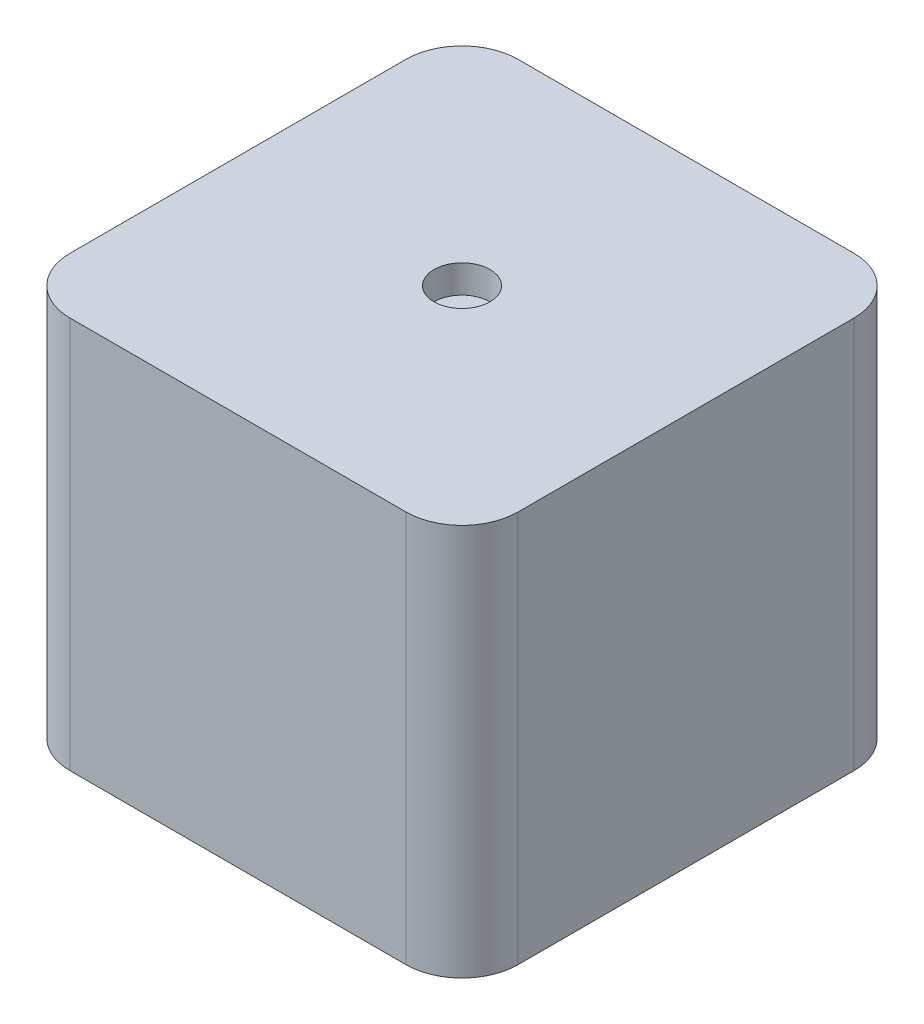
SolidWorks part; units mm, degrees
ref_plane "Front Plane" through (0, 0, 0) normal (0, 0, 1) x (1, 0, 0)
ref_plane "Top Plane" through (0, 0, 0) normal (0, 1, 0) x (1, 0, 0)
ref_plane "Right Plane" through (0, 0, 0) normal (1, 0, 0) x (0, 0, -1)
sketch "Sketch1" plane through (0, 0, 0) normal (0, 1, 0) x (1, 0, 0)
  line L1 (-30, -40) -> (30, -40)
  line L2 (-40, -30) -> (-40, 30)
  line L3 (-30, 40) -> (30, 40)
  line L4 (40, -30) -> (40, 30)
  line L5 (-40, -40) -> (40, 40) construction
  line L6 (-40, 40) -> (40, -40) construction
  arc A0 (-30, -40) -> (-40, -30) centre (-30, -30) cw
  arc A1 (30, -40) -> (40, -30) centre (30, -30) ccw
  arc A2 (30, 40) -> (40, 30) centre (30, 30) cw
  arc A3 (-40, 30) -> (-30, 40) centre (-30, 30) cw
  point P0 (0, 0)
  dimension "D3" = 10
  dimension "D1" = 80
  dimension "D2" = 80
extrude "Boss-Extrude1" add sketch "Sketch1" along normal blind 70
sketch "Sketch2" plane through (0, 70, 0) normal (0, 1, 0) x (1, 0, 0)
  circle A0 centre (0, 0) radius 5
  dimension "D1" = 10
extrude "Cut-Extrude1" cut sketch "Sketch2" against normal blind 5
